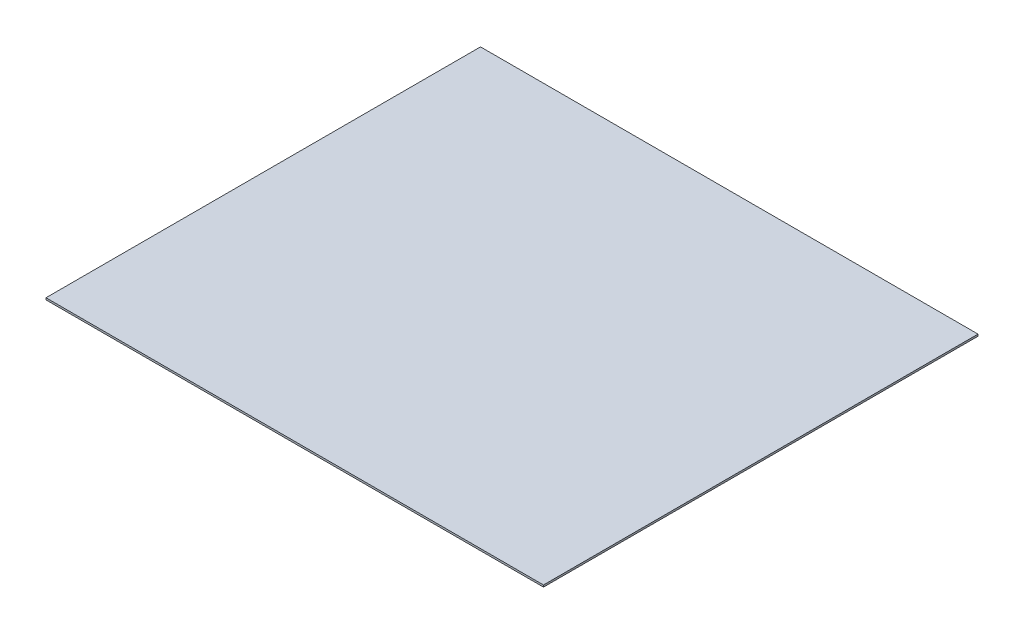
SolidWorks part; units mm, degrees
ref_plane "Front Plane" through (0, 0, 0) normal (0, 0, 1) x (1, 0, 0)
ref_plane "Top Plane" through (0, 0, 0) normal (0, 1, 0) x (1, 0, 0)
ref_plane "Right Plane" through (0, 0, 0) normal (1, 0, 0) x (0, 0, -1)
sketch "Sketch1" plane through (0, 0, 0) normal (0, 1, 0) x (1, 0, 0)
  line L1 (-395, -345) -> (395, -345)
  line L2 (-395, -345) -> (-395, 345)
  line L3 (-395, 345) -> (395, 345)
  line L4 (395, -345) -> (395, 345)
  line L5 (-395, -345) -> (395, 345) construction
  line L6 (-395, 345) -> (395, -345) construction
  point P0 (0, 0)
  dimension "D1" = 790
  dimension "D2" = 690
extrude "Boss-Extrude1" add sketch "Sketch1" along normal blind 3
